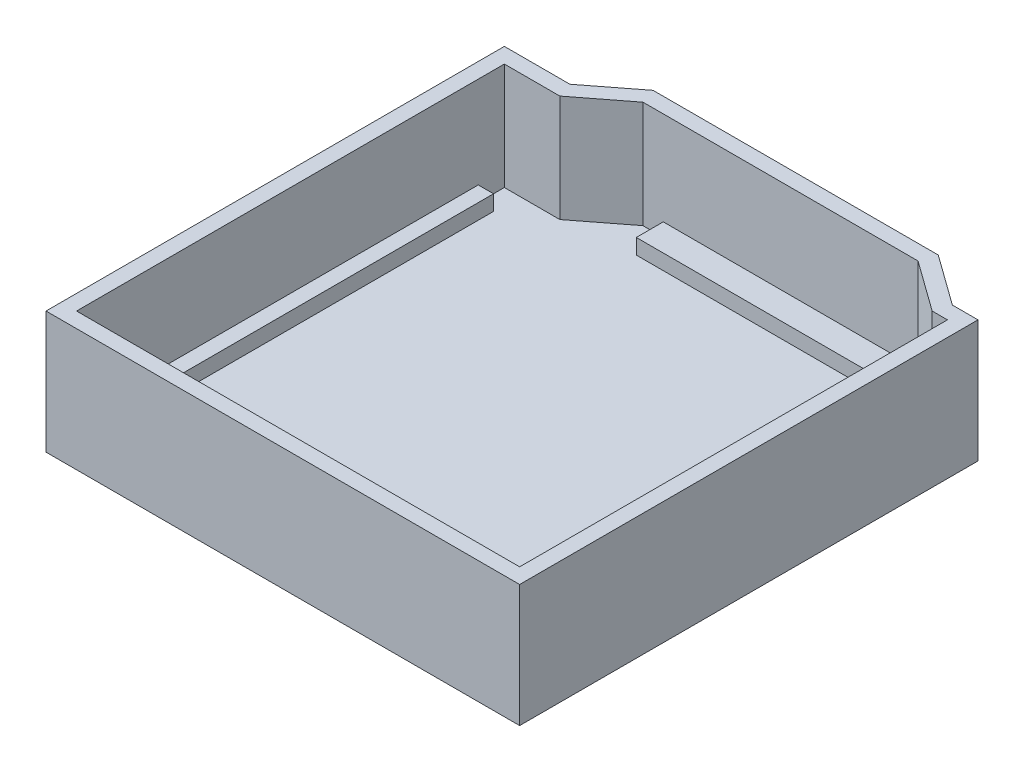
SolidWorks part; units mm, degrees
ref_plane "Front Plane" through (0, 0, 0) normal (0, 0, 1) x (1, 0, 0)
ref_plane "Top Plane" through (0, 0, 0) normal (0, 1, 0) x (1, 0, 0)
ref_plane "Right Plane" through (0, 0, 0) normal (1, 0, 0) x (0, 0, -1)
sketch "Sketch1" plane through (0, 0, 0) normal (0, 1, 0) x (1, 0, 0)
  line L0 (0, 0) -> (0, 56)
  line L1 (0, 56) -> (7.2606, 56)
  line L2 (7.2606, 56) -> (13.3994, 60.7502)
  line L3 (13.3994, 60.7502) -> (49.3994, 60.7502)
  line L4 (0, 0) -> (58, 0)
  line L5 (58, 0) -> (58, 56)
  line L7 (58, 56) -> (56, 56)
  line L8 (56, 56) -> (49.3994, 60.7502)
  dimension "D1" = 56
  dimension "D2" = 58
  dimension "D3" = 2
  dimension "D4" = 36
extrude "Boss-Extrude1" add sketch "Sketch1" along normal blind 14
shell "Shell1" thickness 2
sketch "Sketch3" plane through (0, 0, 0) normal (0, 1, 0) x (1, 0, 0)
  line L0 (0, 56) -> (0, 0) construction
  line L1 (0, 52.5835) -> (2, 52.5835)
  line L2 (0, 52.5835) -> (0, 2.5835)
  line L3 (0, 2.5835) -> (2, 2.5835)
  line L4 (2, 52.5835) -> (2, 2.5835)
  line L7 (57.8762, 52.5835) -> (56.0617, 52.5835)
  line L8 (57.8762, 2.5835) -> (56.0617, 2.5835)
  line L9 (56.0617, 52.5835) -> (56.0617, 2.5835)
  line L10 (57.8762, 52.5835) -> (57.8762, 2.5835)
  dimension "D1" = 2
  dimension "D2" = 50
extrude "Boss-Extrude2" add sketch "Sketch3" along normal blind 2
sketch "Sketch4" plane through (0, 0, 0) normal (0, 1, 0) x (1, 0, 0)
  line L1 (16.2938, 60.5067) -> (47.3114, 60.5067)
  line L2 (16.2938, 60.5067) -> (16.2938, 56.9763)
  line L3 (16.2938, 56.9763) -> (47.3114, 56.9763)
  line L4 (47.3114, 60.5067) -> (47.3114, 56.9763)
extrude "Boss-Extrude3" add sketch "Sketch4" along normal blind 2
